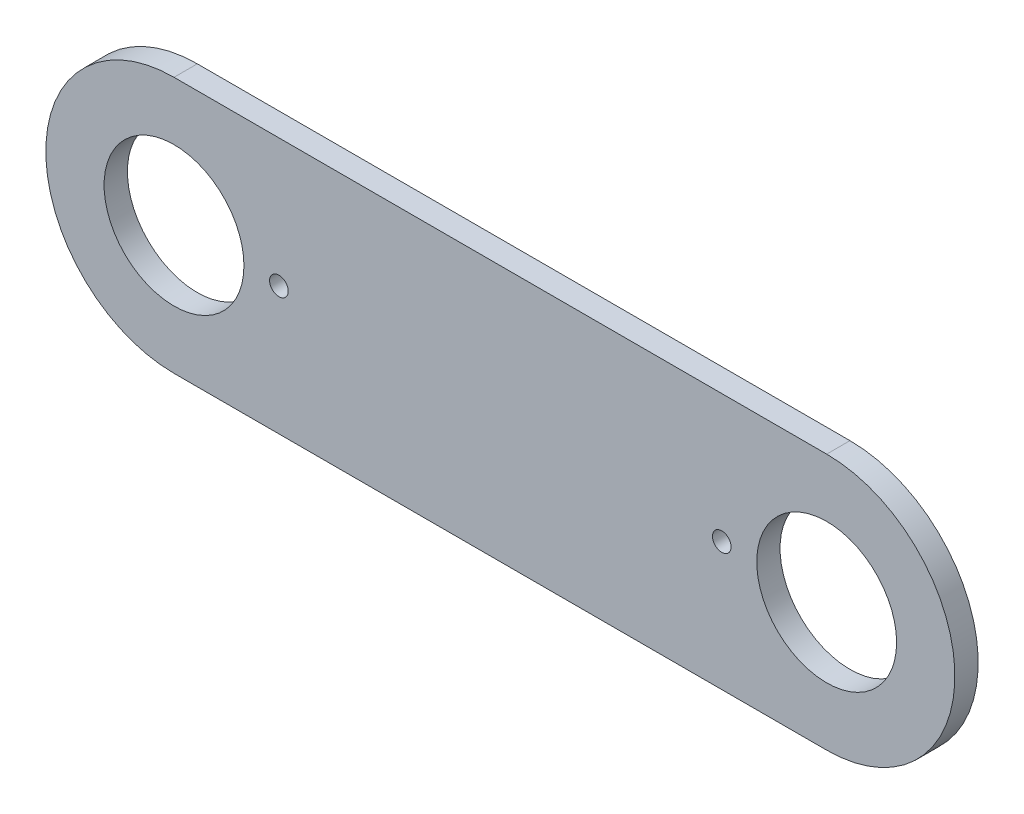
SolidWorks part; units mm, degrees
ref_plane "前视基准面" through (0, 0, 0) normal (0, 0, 1) x (1, 0, 0)
ref_plane "上视基准面" through (0, 0, 0) normal (0, 1, 0) x (1, 0, 0)
ref_plane "右视基准面" through (0, 0, 0) normal (1, 0, 0) x (0, 0, -1)
other "Configuration Table"
sketch "草图1" plane through (0, 0, 0) normal (0, 0, 1) x (1, 0, 0)
  line L0 (0, 0) -> (140, 0) construction
  line L1 (0, 27.5) -> (140, 27.5)
  line L2 (0, -27.5) -> (140, -27.5)
  arc A0 (0, 27.5) -> (0, -27.5) centre (0, 0) ccw
  arc A1 (140, -27.5) -> (140, 27.5) centre (140, 0) ccw
  circle A2 centre (0, 0) radius 15
  circle A3 centre (140, 0) radius 15
  circle A4 centre (0, 0) radius 22.5 construction
  circle A5 centre (140, 0) radius 22.5 construction
  circle A6 centre (22.5, 0) radius 2
  circle A7 centre (117.5, 0) radius 2
  dimension "D1" = 55
  dimension "D2" = 55
  dimension "D4" = 30
  dimension "D5" = 30
  dimension "D6" = 45
  dimension "D7" = 4
  dimension "D8" = 45
  dimension "D9" = 4
  dimension "D3" = 140
extrude "凸台-拉伸1" add sketch "草图1" along normal blind 5
